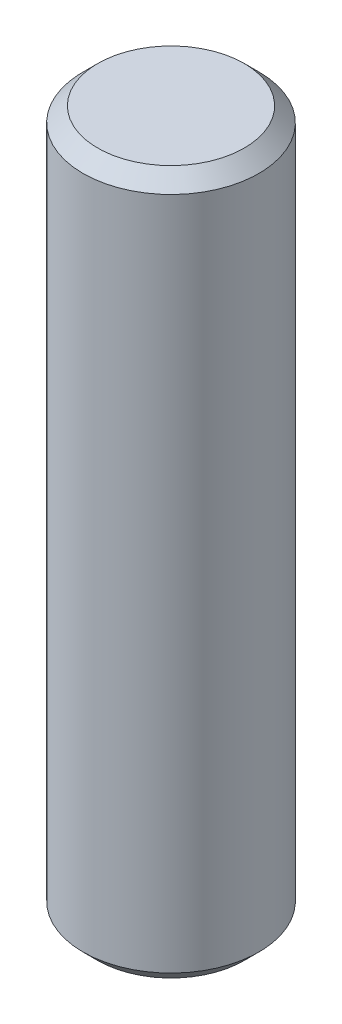
SolidWorks part; units mm, degrees
material "AISI 304"
ref_plane "前视基准面" through (0, 0, 0) normal (0, 0, 1) x (1, 0, 0)
ref_plane "上视基准面" through (0, 0, 0) normal (0, 1, 0) x (1, 0, 0)
ref_plane "右视基准面" through (0, 0, 0) normal (1, 0, 0) x (0, 0, -1)
sketch "草图1" plane through (0, 0, 0) normal (0, 0, 1) x (1, 0, 0)
  line L0 (0, 8.6338) -> (0, -13.0473) construction
  line L1 (0, 0) -> (1.5, 0)
  line L2 (1.5, 0) -> (1.5, 12)
  line L3 (1.5, 12) -> (0, 12)
  line L4 (0, 0) -> (0, 12)
  dimension "D1" = 3
  dimension "D2" = 12
revolve "旋转1" add sketch "草图1" angle 360 about L0
chamfer "倒角1" distance 0.25 angle 45 2 edges at (0, 0, 1.5) (0, 12, 1.5)
